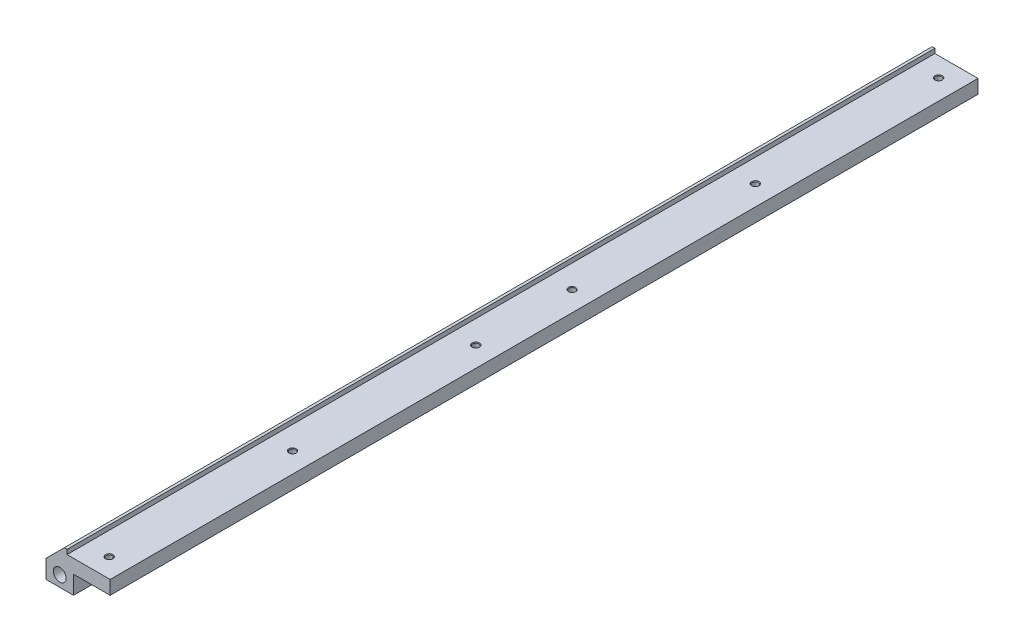
SolidWorks part; units mm, degrees
material "3.1645 (AlCuMgPb) eloxiert"
ref_plane "Vorne" through (0, 0, 0) normal (0, 0, 1) x (1, 0, 0)
ref_plane "Oben" through (0, 0, 0) normal (0, 1, 0) x (1, 0, 0)
ref_plane "Rechts" through (0, 0, 0) normal (1, 0, 0) x (0, 0, -1)
sketch "Skizze1" plane through (0, 0, 0) normal (0, 0, 1) x (1, 0, 0)
  line L0 (8, 28) -> (8, 23)
  line L1 (-15, 28) -> (8, 28)
  line L2 (-15, 28) -> (-15, -12)
  line L3 (-15, -12) -> (55, -12)
  line L4 (55, 23) -> (55, -12)
  line L5 (8, 23) -> (55, 23)
  dimension "D1" = 8
  dimension "D3" = 40
  dimension "D2" = 5
  dimension "D4" = 28
  dimension "D5" = 15
  dimension "D6" = 70
extrude "Linear austragen1" add sketch "Skizze1" along normal mid plane 947
hole_wizard "M8 Gewindebohrung1" positions "Skizze15" profile "Skizze14" tap size "M8" standard "Gabler-Normteile" end condition through all
sketch "Skizze15" plane through (0, 23, 0) normal (0, 1, 0) x (-1, 0, 0)
  line L0 (-8, 473.5) -> (-8, -473.5) construction
  point P0 (-33, 452.5)
  point P2 (-33, -52.5)
  point P9 (-33, 252.5)
  point P10 (-33, -252.5)
  point P11 (-33, 52.5)
  point P12 (-33, -452.5)
  dimension "D2" = 200
  dimension "D3" = 52.5
  dimension "D4" = 52.5
  dimension "D5" = 25
  dimension "D1" = 3
sketch "Skizze14" plane through (33, 23, 452.5) normal (1, 0, 0) x (0, 0, 1)
  line L0 (0, 0) -> (0, 35)
  line L1 (0, 35) -> (3.4, 35)
  line L2 (3.4, 35) -> (3.4, 0.625)
  line L3 (3.4, 0.625) -> (4.025, 0)
  line L5 (4.025, 0) -> (0, 0)
  line L6 (-3.4, 0.625) -> (-4.025, 0) construction
  line L11 (0, -6.35) -> (0, 107.95) construction
  dimension "Bohrerdurchmesser" = 6.8
  dimension "Bohrungstiefe" = 35
  dimension "Senkdurchmesser (Oben)" = 8.05
  dimension "Senkwinkel (Oben)" = 90
cosmetic thread "Bohrungsgewinde3" parameters "D2"=8
cosmetic thread "Bohrungsgewinde4" parameters "D2"=8
cosmetic thread "Bohrungsgewinde5" parameters "D2"=8
cosmetic thread "Bohrungsgewinde6" parameters "D2"=8
cosmetic thread "Bohrungsgewinde7" parameters "D2"=8
cosmetic thread "Bohrungsgewinde8" parameters "D2"=8
sketch "Skizze20" plane through (0, -12, 0) normal (0, -1, 0) x (1, 0, 0)
  line L0 (-15, -473.5) -> (55, -473.5) construction
  line L1 (55, 473.5) -> (15, 473.5)
  line L2 (55, 473.5) -> (55, -473.5)
  line L3 (55, -473.5) -> (15, -473.5)
  line L4 (15, 473.5) -> (15, 373.5)
  line L5 (15, 373.5) -> (11, 373.5)
  line L6 (15, -373.5) -> (11, -373.5)
  line L7 (-10, -352.5) -> (-10, 352.5)
  line L8 (15, -373.5) -> (15, -473.5)
  line L9 (-15, 473.5) -> (-15, -473.5) construction
  arc A0 (11, -373.5) -> (-10, -352.5) centre (11, -352.5) cw
  arc A1 (11, 373.5) -> (-10, 352.5) centre (11, 352.5) ccw
  dimension "D2" = 21
  dimension "D1" = 100
  dimension "D3" = 5
  dimension "D4" = 40
extrude "Schnitt-Linear austragen2" cut sketch "Skizze20" against normal blind 20
chamfer "Fase1" distance 20 angle 45 1 edges at (-15, 28, 0)
hole_wizard "Ø14.0 (14) Durchmesser Bohrung1" positions "Skizze22" profile "Skizze21" hole size "Ø14.0" standard "Gabler-Normteile"
sketch "Skizze22" plane through (0, 0, 473.5) normal (0, 0, 1) x (1, 0, 0)
  point P0 (0, 0)
sketch "Skizze21" plane through (0, 0, 473.5) normal (1, 0, 0) x (0, -1, 0)
  line L0 (0, 0) -> (0, 24.206)
  line L1 (0, 24.206) -> (7, 20)
  line L2 (7, 20) -> (7, 0)
  line L5 (7, 0) -> (0, 0)
  line L10 (0, 24.206) -> (-7, 20) construction
  line L11 (0, -6.35) -> (0, 107.95) construction
  dimension "Bohrerdurchmesser" = 14
  dimension "Bohrungstiefe" = 20
  dimension "Spitzenwinkel" = 118
hole_wizard "Ø14.0 (14) Durchmesser Bohrung2" positions "Skizze24" profile "Skizze23" hole size "Ø14.0" standard "Gabler-Normteile"
sketch "Skizze24" plane through (0, 0, -473.5) normal (0, 0, -1) x (-1, 0, 0)
  point P0 (0, 0)
sketch "Skizze23" plane through (0, 0, -473.5) normal (1, 0, 0) x (0, 1, 0)
  line L0 (0, 0) -> (0, 24.206)
  line L1 (0, 24.206) -> (7, 20)
  line L2 (7, 20) -> (7, 0)
  line L5 (7, 0) -> (0, 0)
  line L10 (0, 24.206) -> (-7, 20) construction
  line L11 (0, -6.35) -> (0, 107.95) construction
  dimension "Bohrerdurchmesser" = 14
  dimension "Bohrungstiefe" = 20
  dimension "Spitzenwinkel" = 118
